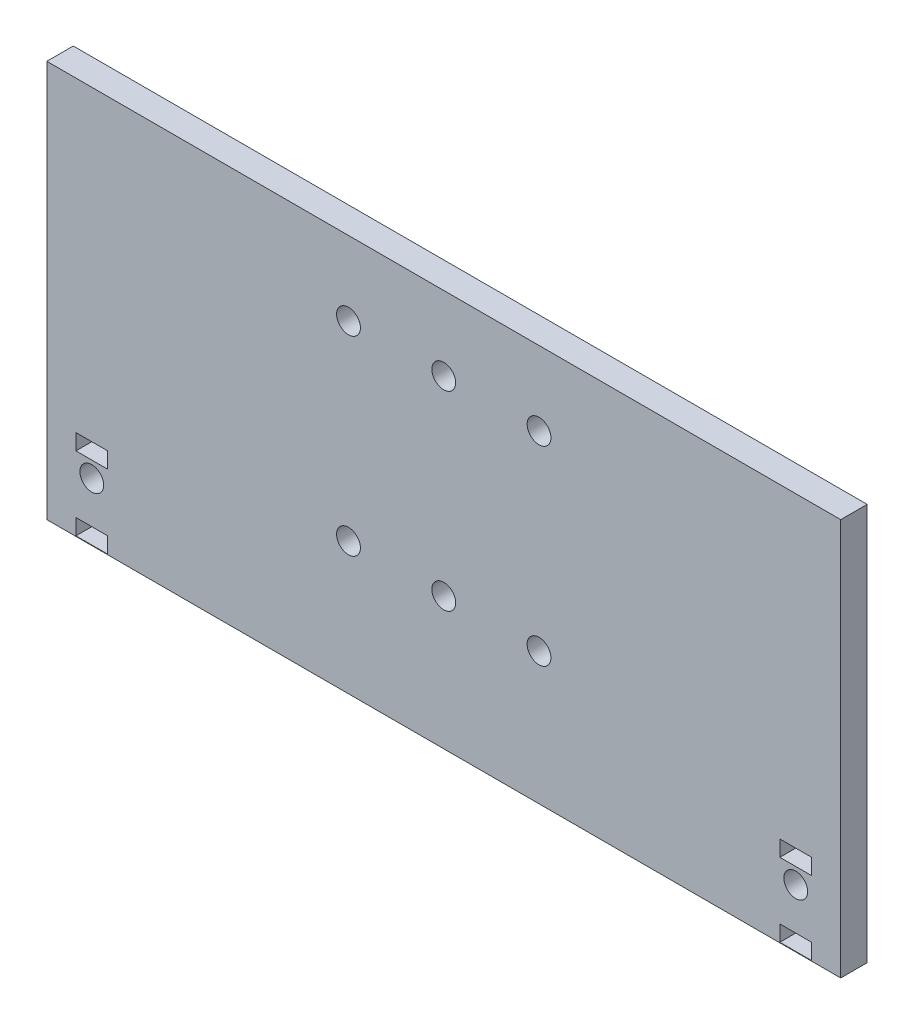
SolidWorks part; units mm, degrees
ref_plane "Plan de face" through (0, 0, 0) normal (0, 0, 1) x (1, 0, 0)
ref_plane "Plan de dessus" through (0, 0, 0) normal (0, 1, 0) x (1, 0, 0)
ref_plane "Plan de droite" through (0, 0, 0) normal (1, 0, 0) x (0, 0, -1)
sketch "Esquisse1" plane through (0, 0, 0) normal (0, 0, 1) x (1, 0, 0)
  line L0 (8.5, -64) -> (141.5, -64) construction
  line L1 (0, 0) -> (150, 0)
  line L2 (0, 0) -> (0, -75)
  line L3 (0, -75) -> (150, -75)
  line L4 (150, 0) -> (150, -75)
  line L5 (75, -14) -> (75, -50) construction
  line L7 (57, -14) -> (93, -14) construction
  line L8 (57, -14) -> (57, -50) construction
  line L9 (57, -50) -> (93, -50) construction
  line L10 (93, -14) -> (93, -50) construction
  line L11 (57, -14) -> (93, -50) construction
  line L12 (57, -50) -> (93, -14) construction
  line L13 (5.5, -58) -> (11.5, -58)
  line L14 (5.5, -58) -> (5.5, -61)
  line L15 (5.5, -61) -> (11.5, -61)
  line L16 (11.5, -58) -> (11.5, -61)
  line L17 (5.5, -71.9) -> (11.5, -71.9)
  line L18 (5.5, -71.9) -> (5.5, -74.9)
  line L19 (5.5, -74.9) -> (11.5, -74.9)
  line L20 (11.5, -71.9) -> (11.5, -74.9)
  line L21 (138.5, -58) -> (144.5, -58)
  line L22 (138.5, -58) -> (138.5, -61)
  line L23 (138.5, -61) -> (144.5, -61)
  line L24 (144.5, -58) -> (144.5, -61)
  line L25 (138.5, -71.9) -> (144.5, -71.9)
  line L26 (138.5, -71.9) -> (138.5, -74.9)
  line L27 (138.5, -74.9) -> (144.5, -74.9)
  line L28 (144.5, -71.9) -> (144.5, -74.9)
  circle A1 centre (8.5, -64) radius 2.25
  circle A2 centre (141.5, -64) radius 2.25
  circle A4 centre (57, -14) radius 2.25
  circle A5 centre (93, -14) radius 2.25
  circle A6 centre (93, -50) radius 2.25
  circle A7 centre (57, -50) radius 2.25
  circle A8 centre (75, -14) radius 2.25
  circle A10 centre (75, -50) radius 2.25
  point P12 (75, -32)
  point P26 (5.5, -59.5)
  point P39 (144.5, -59.5)
  point P40 (11, -75)
  point P41 (6, -75)
  point P42 (6, -75)
  point P43 (11, -75)
  point P44 (5.8587, -75)
  dimension "D3" = 32
  dimension "D4" = 6
  dimension "D6" = 4.5
  dimension "D11" = 4.5
  dimension "D1" = 150
  dimension "D2" = 75
  dimension "D5" = 75
  dimension "D7" = 8.5
  dimension "D8" = 11
  dimension "D9" = 8.5
  dimension "D10" = 3
  dimension "D12" = 36
  dimension "D13" = 36
  dimension "D14" = 17
  dimension "D15" = 5.5
  dimension "D16" = 5.5
  dimension "D17" = 5.5
  dimension "D18" = 5.5
  dimension "D19" = 17
  dimension "D20" = 0.1
  dimension "D21" = 0.1
extrude "Boss.-Extru.1" add sketch "Esquisse1" along normal blind 5
